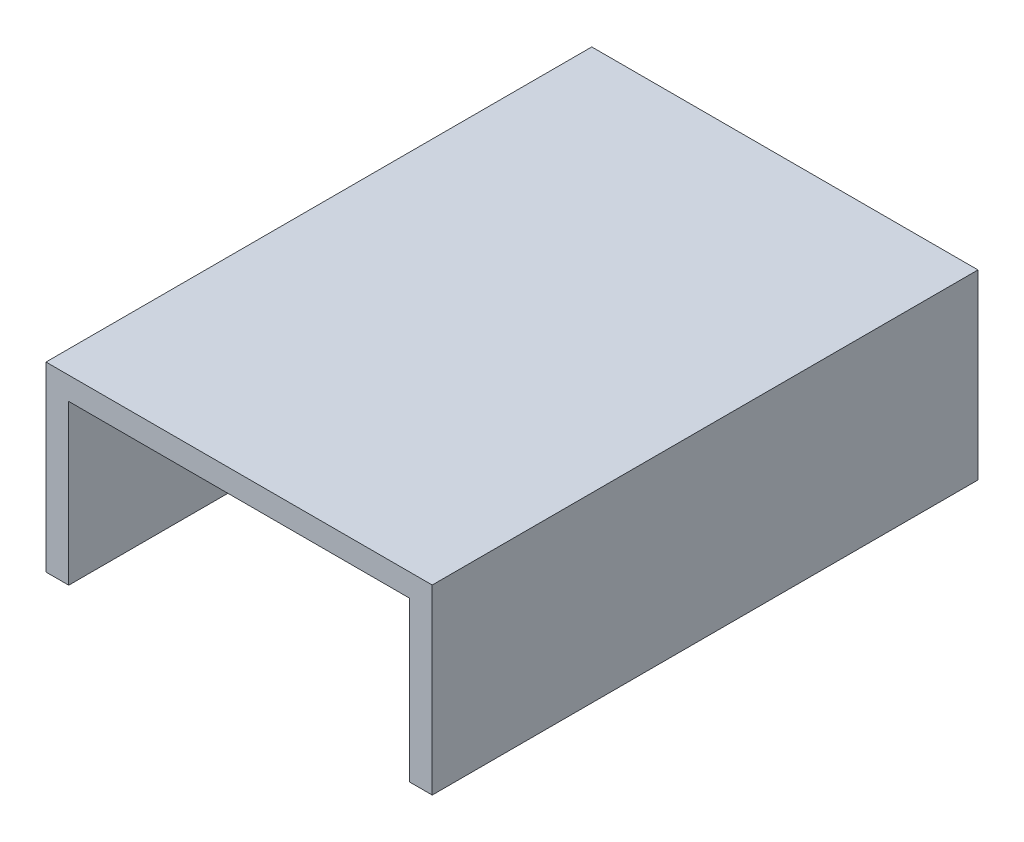
SolidWorks part; units mm, degrees
ref_plane "Front Plane" through (0, 0, 0) normal (0, 0, 1) x (1, 0, 0)
ref_plane "Top Plane" through (0, 0, 0) normal (0, 1, 0) x (1, 0, 0)
ref_plane "Right Plane" through (0, 0, 0) normal (1, 0, 0) x (0, 0, -1)
sketch "Sketch1" plane through (0, 0, 0) normal (0, 0, 1) x (1, 0, 0)
  line L0 (-26.9621, -22.225) -> (-26.9621, 3.175)
  line L1 (-26.9621, 3.175) -> (26.9621, 3.175)
  line L2 (26.9621, 3.175) -> (26.9621, -22.225)
  line L3 (26.9621, -22.225) -> (23.7871, -22.225)
  line L4 (23.7871, -22.225) -> (23.7871, 0)
  line L5 (23.7871, 0) -> (-23.7871, 0)
  line L6 (-23.7871, 0) -> (-23.7871, -22.225)
  line L7 (-23.7871, -22.225) -> (-26.9621, -22.225)
  point P6 (0, 0)
  dimension "D1" = 3.175
  dimension "D2" = 53.9242
  dimension "D3" = 25.4
  dimension "D4" = 3.175
extrude "Boss-Extrude1" add sketch "Sketch1" along normal blind 76.2
